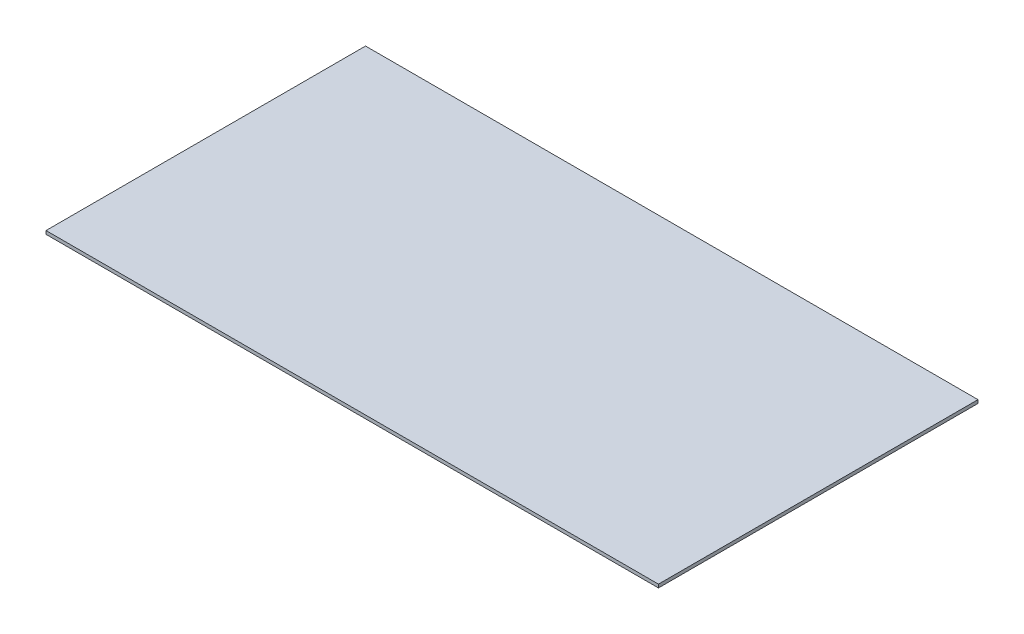
SolidWorks part; units mm, degrees
ref_plane "Front Plane" through (0, 0, 0) normal (0, 0, 1) x (1, 0, 0)
ref_plane "Top Plane" through (0, 0, 0) normal (0, 1, 0) x (1, 0, 0)
ref_plane "Right Plane" through (0, 0, 0) normal (1, 0, 0) x (0, 0, -1)
sketch "Sketch1" plane through (0, 0, 0) normal (0, 1, 0) x (1, 0, 0)
  line L1 (-584.2, -304.8) -> (584.2, -304.8)
  line L2 (-584.2, -304.8) -> (-584.2, 304.8)
  line L3 (-584.2, 304.8) -> (584.2, 304.8)
  line L4 (584.2, -304.8) -> (584.2, 304.8)
  line L5 (-584.2, -304.8) -> (584.2, 304.8) construction
  line L6 (-584.2, 304.8) -> (584.2, -304.8) construction
  point P0 (0, 0)
  dimension "D1" = 1168.4
  dimension "D2" = 609.6
extrude "Boss-Extrude1" add sketch "Sketch1" along normal blind 6.35
